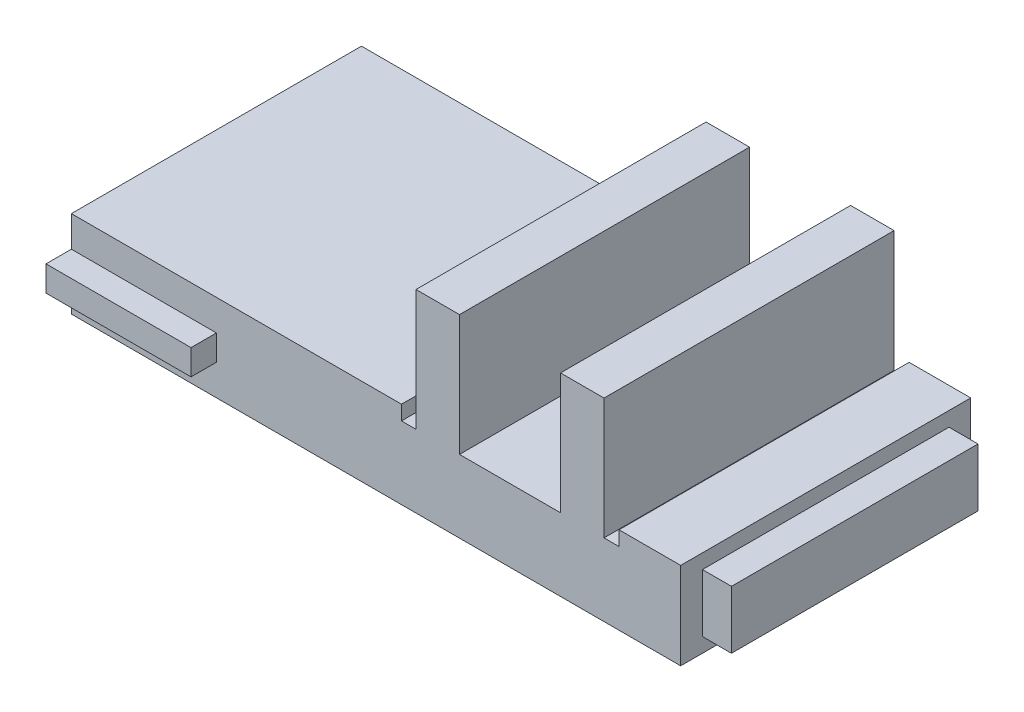
SolidWorks part; units mm, degrees
ref_plane "Front Plane" through (0, 0, 0) normal (0, 0, 1) x (1, 0, 0)
ref_plane "Top Plane" through (0, 0, 0) normal (0, 1, 0) x (1, 0, 0)
ref_plane "Right Plane" through (0, 0, 0) normal (1, 0, 0) x (0, 0, -1)
sketch "Sketch2" plane through (0, 0, 0) normal (0, 0, 1) x (1, 0, 0)
  line L0 (-7.5, 1) -> (-30.26, 1)
  line L1 (-30.26, 1) -> (-30.26, -5)
  line L2 (-30.26, -5) -> (11.75, -5)
  line L3 (11.75, -5) -> (11.75, 1)
  line L4 (11.75, 1) -> (7.5, 1)
  line L5 (7.5, 1) -> (7.5, 0)
  line L6 (7.5, 0) -> (-7.5, 0)
  line L7 (-7.5, 0) -> (-7.5, 1)
  point P2 (0, 0)
  dimension "D1" = 22.76
  dimension "D2" = 5
  dimension "D3" = 1
  dimension "D4" = 15
  dimension "D5" = 4.25
extrude "Boss-Extrude1" add sketch "Sketch2" along normal blind 20
sketch "Sketch6" plane through (11.75, 0, 0) normal (1, 0, 0) x (0, 0, -1)
  line L0 (-20, 1) -> (0, 1) construction
  line L1 (-18.5, 0) -> (-1.5, 0)
  line L2 (-18.5, 0) -> (-18.5, -4)
  line L3 (-18.5, -4) -> (-1.5, -4)
  line L4 (-1.5, 0) -> (-1.5, -4)
  line L5 (-18.5, 0) -> (-1.5, -4) construction
  line L6 (-18.5, -4) -> (-1.5, 0) construction
  line L7 (0, -5) -> (0, 1) construction
  point P0 (-10, -2)
  point P9 (-10, 1)
  point P12 (0, -2)
  dimension "D1" = 4
  dimension "D2" = 17
extrude "Boss-Extrude3" add sketch "Sketch6" along normal blind 2
sketch "Sketch7" plane through (0, 0, 0) normal (0, 1, 0) x (1, 0, 0)
  line L1 (-6.5, 0) -> (-3.5, 0)
  line L2 (-6.5, 0) -> (-6.5, -20)
  line L3 (-6.5, -20) -> (-3.5, -20)
  line L4 (-3.5, 0) -> (-3.5, -20)
  line L5 (-6.5, 0) -> (-3.5, -20) construction
  line L6 (-6.5, -20) -> (-3.5, 0) construction
  line L8 (3.4659, 0) -> (6.4659, 0)
  line L9 (3.4659, 0) -> (3.4659, -20)
  line L10 (7.5, 0) -> (-7.5, 0) construction
  line L11 (7.5, -20) -> (-7.5, -20) construction
  line L12 (3.4659, -20) -> (6.4659, -20)
  line L13 (0, 0) -> (0, -20) construction
  line L18 (-7.5, -20) -> (-7.5, 0) construction
  line L19 (6.4659, 0) -> (6.4659, -20)
  line L20 (3.4659, 0) -> (6.4659, -20) construction
  line L21 (3.4659, -20) -> (6.4659, 0) construction
  point P0 (-5, -10)
  point P5 (4.9659, -10)
  point P19 (6.2159, 0)
  dimension "D1" = 3
  dimension "D2" = 1
  dimension "D3" = 20
  dimension "D4" = 6.9659
extrude "Boss-Extrude4" add sketch "Sketch7" along normal blind 8.35
sketch "Sketch8" plane through (-30.26, 0, 0) normal (-1, 0, 0) x (0, 0, 1)
  line L0 (0, 1) -> (0, -5) construction
  line L1 (-1.75, -1.125) -> (0, -1.125)
  line L2 (-1.75, -1.125) -> (-1.75, -2.875)
  line L3 (-1.75, -2.875) -> (0, -2.875)
  line L4 (0, -1.125) -> (0, -2.875)
  line L5 (-1.75, -1.125) -> (0, -2.875) construction
  line L6 (-1.75, -2.875) -> (0, -1.125) construction
  line L7 (10, 1) -> (10, -5) construction
  line L8 (20, 1) -> (0, 1) construction
  line L9 (20, -5) -> (0, -5) construction
  line L10 (21.75, -2.875) -> (20, -1.125) construction
  line L11 (21.75, -1.125) -> (20, -2.875) construction
  line L12 (20, -1.125) -> (20, -2.875)
  line L13 (21.75, -2.875) -> (20, -2.875)
  line L14 (21.75, -1.125) -> (21.75, -2.875)
  line L15 (21.75, -1.125) -> (20, -1.125)
  point P0 (-0.875, -2)
  point P7 (0, -2)
  point P8 (0, -2)
  point P19 (20.875, -2)
  dimension "D1" = 1.75
extrude "Boss-Extrude5" add sketch "Sketch8" against normal blind 10
